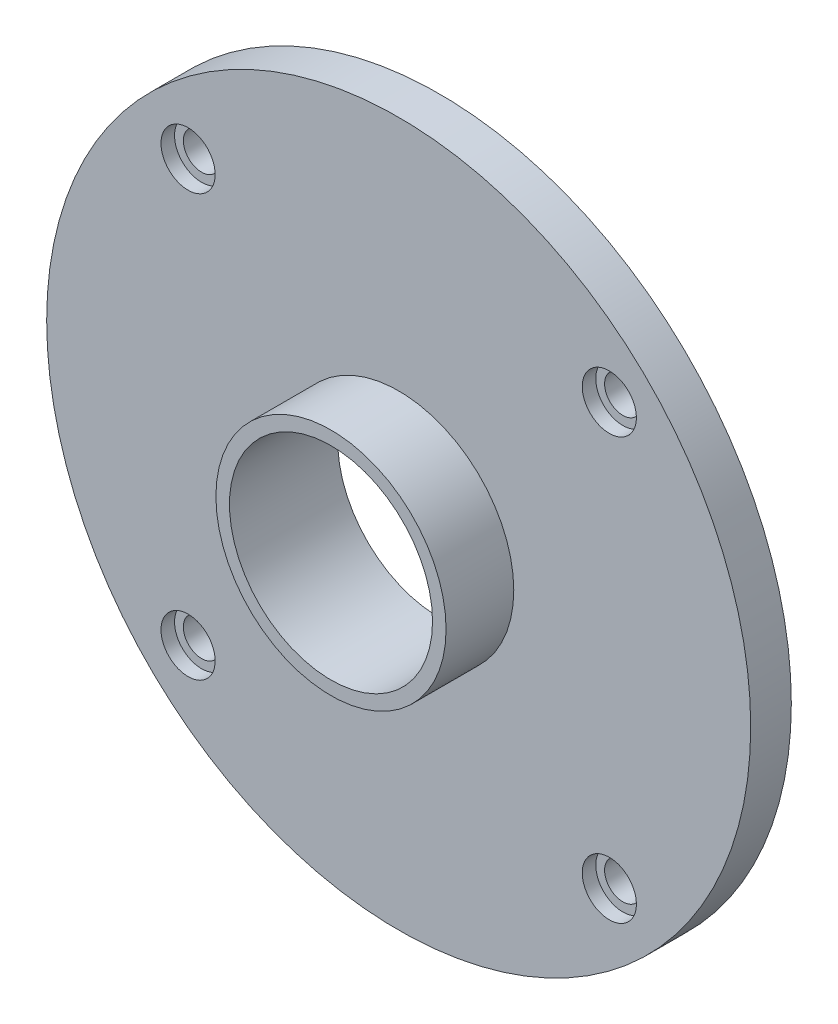
SolidWorks part; units mm, degrees
ref_plane "Спереди" through (0, 0, 0) normal (0, 0, 1) x (1, 0, 0)
ref_plane "Сверху" through (0, 0, 0) normal (0, 1, 0) x (1, 0, 0)
ref_plane "Справа" through (0, 0, 0) normal (1, 0, 0) x (0, 0, -1)
sketch "Эскиз1" plane through (0, 0, 0) normal (0, 0, 1) x (1, 0, 0)
  circle A0 centre (0, 0) radius 26
  dimension "D1" = 52
extrude "Бобышка-Вытянуть1" add sketch "Эскиз1" along normal blind 3
sketch "Эскиз2" plane through (0, 0, 3) normal (0, 0, 1) x (1, 0, 0)
  circle A0 centre (0, 0) radius 7.5
  dimension "D1" = 15
extrude "Вырез-Вытянуть1" cut sketch "Эскиз2" against normal through all
sketch "Эскиз3" plane through (0, 0, 3) normal (0, 0, 1) x (1, 0, 0)
  circle A0 centre (0, 0) radius 8.5
  circle A2 centre (0, 0) radius 7.5
  dimension "D1" = 17
  dimension "D2" = 15
extrude "Бобышка-Вытянуть3" add sketch "Эскиз3" along normal blind 5
sketch "Эскиз4" plane through (0, 0, 3) normal (0, 0, 1) x (1, 0, 0)
  line L0 (0, 0) -> (-54.9164, 0) construction
  line L1 (0, 0) -> (-42.4264, 42.4264) construction
  circle A0 centre (0, 0) radius 26 construction
  circle A5 centre (-15.5563, 15.5563) radius 1.35
  circle A6 centre (15.5563, 15.5563) radius 1.35
  circle A7 centre (15.5563, -15.5563) radius 1.35
  circle A8 centre (-15.5563, -15.5563) radius 1.35
  point P16 (0, 0)
  point P17 (0, 0)
  dimension "D1" = 52
  dimension "D3" = 2.7
  dimension "D2" = 45
  dimension "D5" = 4
  dimension "D4" = 22
extrude "Вырез-Вытянуть2" cut sketch "Эскиз4" against normal through all
sketch "Эскиз5" plane through (0, 0, 3) normal (0, 0, 1) x (1, 0, 0)
  circle A0 centre (-15.5563, 15.5563) radius 2
  circle A1 centre (15.5563, 15.5563) radius 2
  circle A2 centre (15.5563, -15.5563) radius 2
  circle A3 centre (-15.5563, -15.5563) radius 2
  point P12 (0, 0)
  dimension "D1" = 4
  dimension "D2" = 4
extrude "Вырез-Вытянуть3" cut sketch "Эскиз5" against normal blind 1
